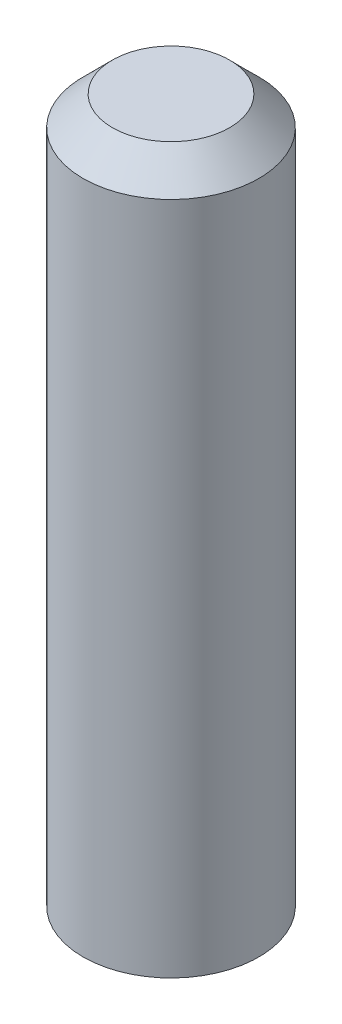
SolidWorks part; units mm, degrees
ref_plane "Front Plane" through (0, 0, 0) normal (0, 0, 1) x (1, 0, 0)
ref_plane "Top Plane" through (0, 0, 0) normal (0, 1, 0) x (1, 0, 0)
ref_plane "Right Plane" through (0, 0, 0) normal (1, 0, 0) x (0, 0, -1)
sketch "Sketch1" plane through (0, 0, 0) normal (0, 1, 0) x (1, 0, 0)
  circle A0 centre (0, 0) radius 3
  dimension "D1" = 6
extrude "Boss-Extrude1" add sketch "Sketch1" along normal blind 24
chamfer "Chamfer1" distance 1 angle 45 1 edges at (0, 24, 3)
hole_wizard "M4x0.7 Tapped Hole1" positions "Sketch2" profile "Sketch3" tap size "M4x0.7" standard "ANSI Metric"
sketch "Sketch2" plane through (0, 0, 0) normal (0, -1, 0) x (1, 0, 0)
  point P0 (0, 0)
sketch "Sketch3" plane through (0, 0, 0) normal (1, 0, 0) x (0, 0, -1)
  line L0 (0, 0) -> (0, 6.9914)
  line L1 (0, 6.9914) -> (1.65, 6)
  line L2 (1.65, 6) -> (1.65, 0)
  line L5 (1.65, 0) -> (0, 0)
  line L10 (0, 6.9914) -> (-1.65, 6) construction
  line L11 (0, -6.35) -> (0, 107.95) construction
  dimension "Tap Drill Dia." = 3.3
  dimension "Tap Drill Depth" = 6
  dimension "Drill Angle" = 118
